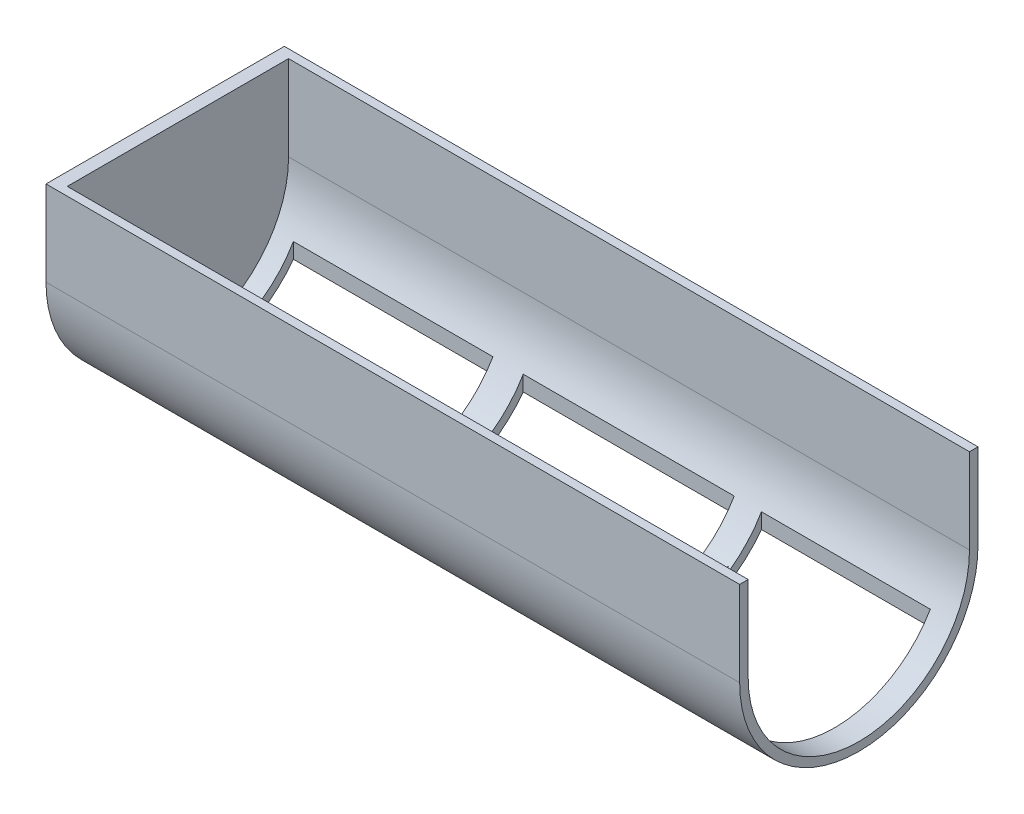
SolidWorks part; units mm, degrees
ref_plane "Front Plane" through (0, 0, 0) normal (0, 0, 1) x (1, 0, 0)
ref_plane "Top Plane" through (0, 0, 0) normal (0, 1, 0) x (1, 0, 0)
ref_plane "Right Plane" through (0, 0, 0) normal (1, 0, 0) x (0, 0, -1)
sketch "Sketch1" plane through (0, 0, 0) normal (1, 0, 0) x (0, 0, -1)
  line L0 (26, 0) -> (28, 0)
  line L5 (-28, 0) -> (-26, 0)
  arc A0 (26, 0) -> (-26, 0) centre (0, 0) cw
  arc A1 (28, 0) -> (-28, 0) centre (0, 0) cw
  dimension "D3" = 26
  dimension "D1" = 2
extrude "Boss-Extrude1" add sketch "Sketch1" along normal blind 160
sketch "Sketch2" plane through (0, 0, 0) normal (0, 1, 0) x (1, 0, 0)
  line L4 (0, 28) -> (0, 26)
  line L5 (0, 26) -> (160, 26)
  line L6 (160, 26) -> (160, 28)
  line L7 (160, 28) -> (0, 28)
  line L8 (0, 28) -> (0, 26)
  line L9 (0, 26) -> (160, 26)
  line L10 (160, 26) -> (160, 28)
  line L11 (160, 28) -> (0, 28)
  line L12 (0, -26) -> (0, -28)
  line L13 (0, -28) -> (160, -28)
  line L14 (160, -28) -> (160, -26)
  line L15 (160, -26) -> (0, -26)
  line L16 (0, -26) -> (0, -28)
  line L17 (0, -28) -> (160, -28)
  line L18 (160, -28) -> (160, -26)
  line L19 (160, -26) -> (0, -26)
  dimension "D1" = 0
  dimension "D2" = 0
extrude "Boss-Extrude2" add sketch "Sketch2" along normal blind 20
sketch "Sketch3" plane through (0, 0, 0) normal (-1, 0, 0) x (0, 0, 1)
  line L1 (-28, 20) -> (28, 20)
  line L2 (-28, 20) -> (-28, 0)
  line L4 (28, 20) -> (28, 0)
  arc A0 (-28, 0) -> (28, 0) centre (0, 0) ccw
  arc A1 (-28, 0) -> (28, 0) centre (0, 0) ccw construction
extrude "Boss-Extrude3" add sketch "Sketch3" along normal blind 3
sketch "Sketch4" plane through (0, 20, 0) normal (0, 1, 0) x (1, 0, 0)
  line L1 (4.6733, -18.9962) -> (51.561, -18.9962)
  line L2 (4.6733, -18.9962) -> (4.6733, 22.4535)
  line L3 (4.6733, 22.4535) -> (51.561, 22.4535)
  line L4 (51.561, -18.9962) -> (51.561, 22.4535)
  line L5 (58.683, -17.2446) -> (108.2613, -17.2446)
  line L6 (58.683, -17.2446) -> (58.683, 22.4535)
  line L7 (58.683, 22.4535) -> (108.2613, 22.4535)
  line L8 (108.2613, -17.2446) -> (108.2613, 22.4535)
  line L9 (114.6625, -17.2446) -> (154.3361, -17.2446)
  line L10 (114.6625, -17.2446) -> (114.6625, 22.4535)
  line L11 (114.6625, 22.4535) -> (154.3361, 22.4535)
  line L12 (154.3361, -17.2446) -> (154.3361, 22.4535)
extrude "Cut-Extrude1" cut sketch "Sketch4" against normal through all
